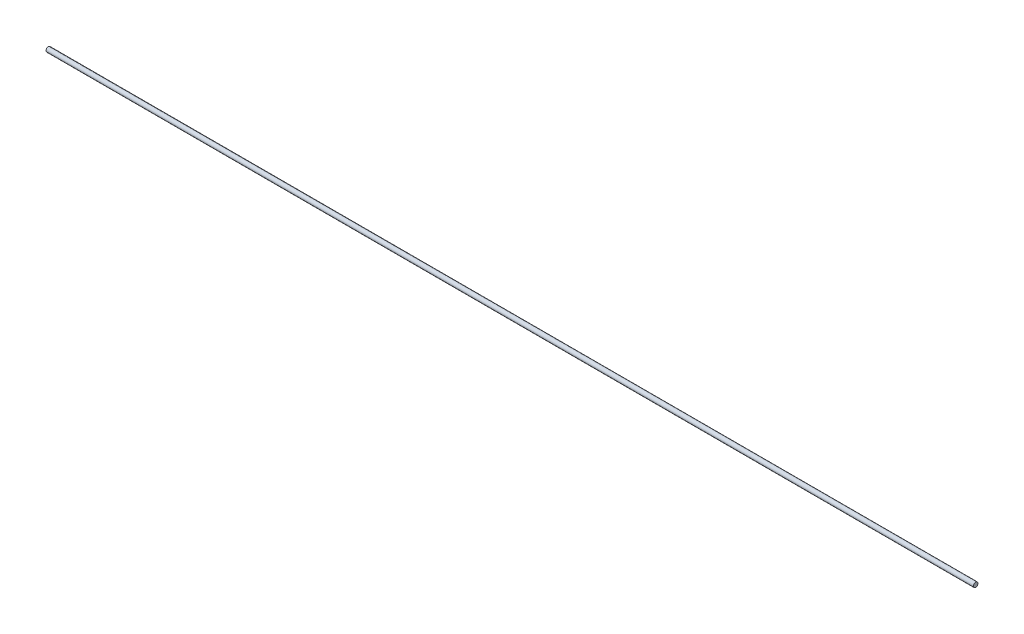
SolidWorks part; units mm, degrees
material "Copper"
ref_plane "Front Plane" through (0, 0, 0) normal (0, 0, 1) x (1, 0, 0)
ref_plane "Top Plane" through (0, 0, 0) normal (0, 1, 0) x (1, 0, 0)
ref_plane "Right Plane" through (0, 0, 0) normal (1, 0, 0) x (0, 0, -1)
sketch "Sketch1" plane through (0, 0, 0) normal (1, 0, 0) x (0, 0, -1)
  circle A0 centre (0, 0) radius 0.125
  dimension "D1" = 0.25
extrude "Boss-Extrude1" add sketch "Sketch1" along normal blind 50
